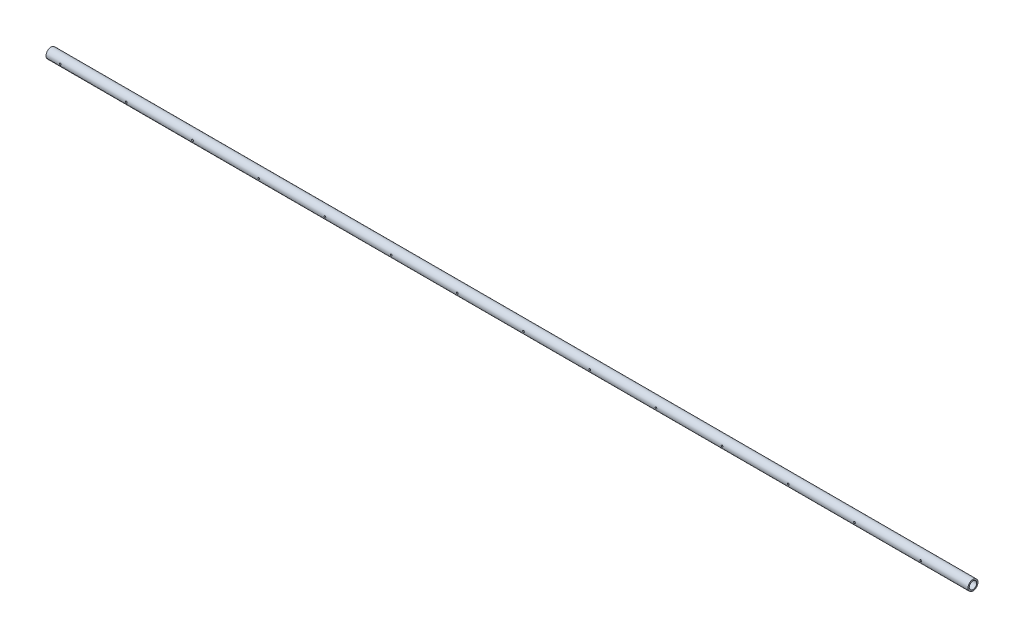
SolidWorks part; units mm, degrees
material "AISI 316  (SS)"
ref_plane "Front Plane" through (0, 0, 0) normal (0, 0, 1) x (1, 0, 0)
ref_plane "Top Plane" through (0, 0, 0) normal (0, 1, 0) x (1, 0, 0)
ref_plane "Right Plane" through (0, 0, 0) normal (1, 0, 0) x (0, 0, -1)
sketch "Sketch1" plane through (0, 0, 0) normal (1, 0, 0) x (0, 0, -1)
  circle A0 centre (0, 0) radius 10.65
  circle A1 centre (0, 0) radius 7.88
  dimension "D1" = 21.3
  dimension "D2" = 2.77
extrude "Boss-Extrude1" add sketch "Sketch1" along normal blind 1950
sketch "Sketch2" plane through (0, 0, 0) normal (0, 0, 1) x (1, 0, 0)
  line L0 (1950, -10.65) -> (1950, 10.65) construction
  circle A0 centre (1850, 0) radius 1.85
  dimension "D1" = 3.7
  dimension "D2" = 100
extrude "Cut-Extrude1" cut sketch "Sketch2" along normal blind 40
pattern_linear "LPattern1" count 14 spacing 140 along (-1, 0, 0) of "Cut-Extrude1"
